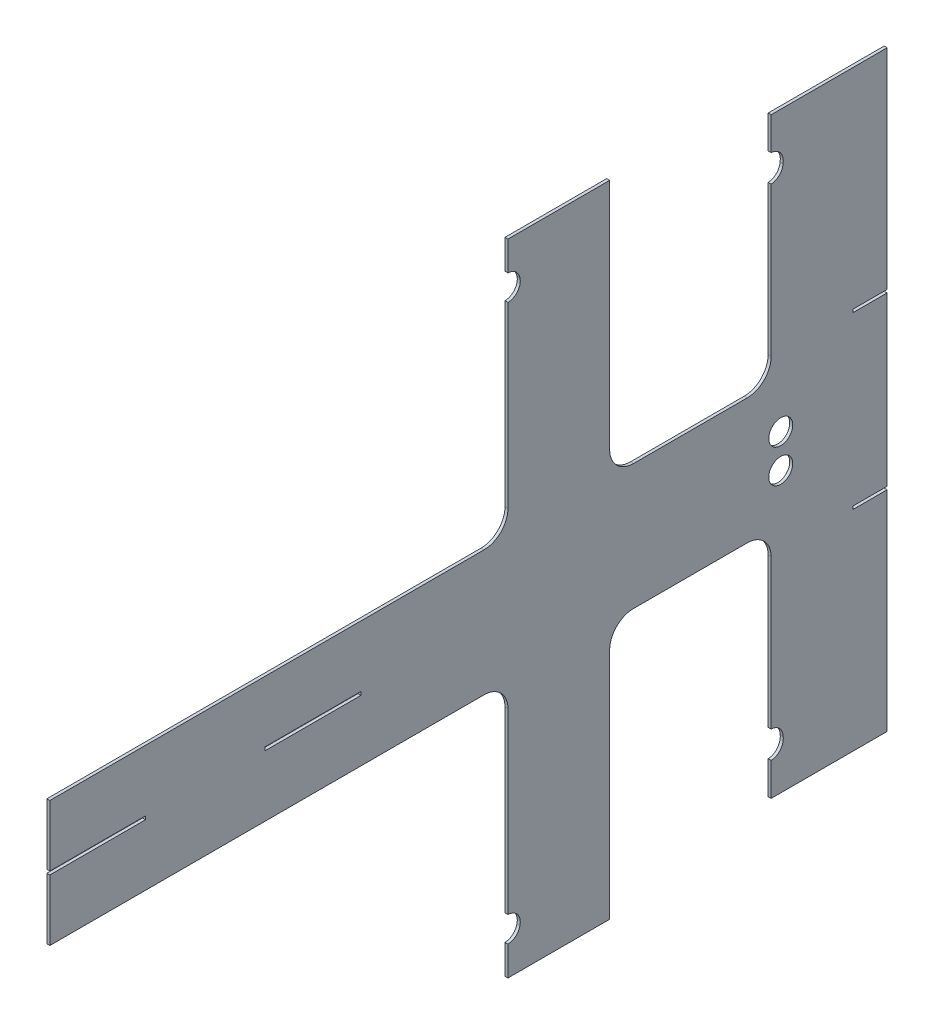
SolidWorks part; units mm, degrees
material "Custom Plastic"
ref_plane "X-Y Datum" through (0, 0, 0) normal (0, 0, 1) x (1, 0, 0)
ref_plane "X-Z Datum" through (0, 0, 0) normal (0, 1, 0) x (1, 0, 0)
ref_plane "Y-Z Datum" through (0, 0, 0) normal (1, 0, 0) x (0, 0, -1)
ref_plane "Plane1" through (523.5321, 0, 0) normal (-1, 0, 0) x (0, 0, 1)
sketch "Sketch1" plane through (523.5321, 0, 0) normal (-1, 0, 0) x (0, 0, 1)
  line L0 (-139.7, 314.325) -> (-16.51, 314.325)
  line L1 (-16.51, 314.325) -> (-16.51, 66.675)
  line L2 (-103.1775, -92.075) -> (-103.1775, -88.9)
  line L3 (-103.1775, 88.9) -> (-103.1775, 92.075)
  line L4 (-103.1775, -88.9) -> (-139.7, -88.9)
  line L5 (-139.7, -88.9) -> (-139.7, 88.9)
  line L6 (-139.7, 88.9) -> (-103.1775, 88.9)
  line L7 (-103.1775, 92.075) -> (-139.7, 92.075)
  line L8 (-103.1775, -92.075) -> (-139.7, -92.075)
  line L9 (-139.7, 92.075) -> (-139.7, 314.325)
  line L10 (-139.7, -92.075) -> (-139.7, -314.325)
  line L11 (-139.7, -314.325) -> (-16.51, -314.325)
  line L12 (-16.51, -314.325) -> (-16.51, -66.675)
  line L13 (-16.51, -66.675) -> (154.94, -66.675)
  line L14 (749.3, -66.675) -> (749.3, 66.675)
  line L15 (749.3, 66.675) -> (262.89, 66.675)
  line L16 (262.89, 339.725) -> (262.89, 66.675)
  line L17 (262.89, 339.725) -> (154.94, 339.725)
  line L18 (154.94, 339.725) -> (154.94, 66.675)
  line L19 (262.89, -66.675) -> (262.89, -339.725)
  line L20 (262.89, -339.725) -> (154.94, -339.725)
  line L21 (154.94, -339.725) -> (154.94, -66.675)
  line L22 (262.89, -66.675) -> (749.3, -66.675)
  line L23 (154.94, 66.675) -> (-16.51, 66.675)
  dimension "D1" = 177.8
  dimension "D2" = 184.15
  dimension "D3" = 36.5225
  dimension "D4" = 36.5225
  dimension "D5" = 3.175
  dimension "D6" = 3.175
  dimension "D7" = 222.25
  dimension "D8" = 123.19
  dimension "D9" = 247.65
  dimension "D10" = 222.25
  dimension "D11" = 171.45
  dimension "D12" = 279.4
  dimension "D13" = 107.95
  dimension "D14" = 273.05
extrude "Boss-Extrude1" add sketch "Sketch1" along normal mid plane 3.175 contours L15 L16 L17 L18 L23 L1 L0 L9 L7 L3 L6 L5 L4 L2 L8 L10 L11 L12 L13 L21 L20 L19 L22 L14
ref_plane "Plane2" through (906.3228, 136.1666, 0) normal (0.9471, -0.3184, 0.0399) x (0.0378, -0.0127, -0.9992)
sketch "Sketch2" plane through (906.3228, 136.1666, 0) normal (0.9471, -0.3184, 0.0399) x (0.0378, -0.0127, -0.9992)
  circle A0 centre (0, 0) radius 13.081
  dimension "D1" = 26.162
extrude "Cut-Extrude1" cut sketch "Sketch2" against normal up to surface (410.2408 mm away)
sketch "Sketch5" plane through (525.1196, 0, 0) normal (1, 0, 0) x (0, 0, -1)
  ellipse E0 centre (16.0688, 264.3155) end of major axis (16.51, 250.5304) minor radius 13.2132
extrude "Cut-Extrude3" cut sketch "Sketch5" against normal through all
sketch "Sketch7" plane through (521.9446, 0, 0) normal (-1, 0, 0) x (0, 0, 1)
  ellipse E0 centre (-16.2026, 265.3828) end of major axis (-16.51, 279.1825) minor radius 13.0881
extrude "Cut-Extrude6" cut sketch "Sketch7" against normal through all
sketch "Sketch9" plane through (525.1196, 0, 0) normal (1, 0, 0) x (0, 0, -1)
  line L1 (16.51, 314.325) -> (16.51, 279.1825) construction
  ellipse E0 centre (16.2026, 265.3828) end of major axis (16.51, 279.366) minor radius 13.2029
extrude "Cut-Extrude9" cut sketch "Sketch9" against normal through all
ref_plane "Plane3" through (906.3228, 241.3, 254) normal (-0.9901, 0.1386, 0.0235) x (0.0233, -0.0033, 0.9997)
sketch "Sketch10" plane through (906.3228, 241.3, 254) normal (-0.9901, 0.1386, 0.0235) x (0.0233, -0.0033, 0.9997)
  circle A0 centre (0, 0) radius 13.081
  dimension "D1" = 26.162
extrude "Cut-Extrude10" cut sketch "Sketch10" along normal up to surface (386.4019 mm away)
sketch "Sketch12" plane through (525.1196, 0, 0) normal (1, 0, 0) x (0, 0, -1)
  ellipse E0 centre (-263.0633, 294.6624) end of major axis (-262.89, 281.4545) minor radius 13.0841
extrude "Cut-Extrude11" cut sketch "Sketch12" against normal through all
sketch "Sketch13" plane through (521.9446, 0, 0) normal (-1, 0, 0) x (0, 0, 1)
  line L0 (262.89, 339.725) -> (262.89, 308.3121) construction
  ellipse E0 centre (263.1388, 295.1069) end of major axis (262.89, 308.5494) minor radius 13.1927
extrude "Cut-Extrude12" cut sketch "Sketch13" against normal through all
sketch "Sketch15" plane through (525.1196, 0, 0) normal (1, 0, 0) x (0, 0, -1)
  line L0 (-262.89, 281.4545) -> (-262.89, 66.675) construction
  ellipse E0 centre (-263.0633, 294.6624) end of major axis (-262.89, 281.4162) minor radius 13.2333
extrude "Cut-Extrude13" cut sketch "Sketch15" against normal through all
mirror "Mirror1" about plane through (0, 0, 0) normal (0, 1, 0) of "Cut-Extrude13", "Cut-Extrude12", "Cut-Extrude11", "Cut-Extrude10", "Cut-Extrude9", "Cut-Extrude6", "Cut-Extrude3", "Cut-Extrude1"
fillet "Fillet1" radius 25.4 6 edges at (523.5321, 66.675, 262.89) (523.5321, -66.675, 262.89) (523.5321, -66.675, 154.94) (523.5321, -66.675, -16.51) (523.5321, 66.675, 154.94) (523.5321, 66.675, -16.51)
sketch "Sketch16" plane through (525.1196, 0, 0) normal (1, 0, 0) x (0, 0, -1)
  line L0 (-520.7, 0) -> (-419.1, 0) construction
  line L1 (-419.1, -1.7907) -> (-419.1, 1.7907)
  line L2 (-520.7, -1.7907) -> (-520.7, 1.7907)
  line L3 (-520.7, 1.7907) -> (-419.1, 1.7907)
  line L4 (-419.1, -1.7907) -> (-520.7, -1.7907)
  line L28 (-262.89, -308.5494) -> (-262.89, -339.725)
  line L29 (-262.89, -339.725) -> (-154.94, -339.725)
  line L30 (-154.94, -339.725) -> (-154.94, -92.075)
  line L31 (-129.54, -66.675) -> (-8.89, -66.675)
  line L32 (16.51, -92.075) -> (16.51, -250.5304)
  line L33 (16.51, -279.366) -> (16.51, -314.325)
  line L34 (16.51, -314.325) -> (139.7, -314.325)
  line L35 (139.7, -314.325) -> (139.7, -92.075)
  line L36 (139.7, -92.075) -> (103.1775, -92.075)
  line L37 (103.1775, -92.075) -> (103.1775, -88.9)
  line L38 (103.1775, -88.9) -> (139.7, -88.9)
  line L39 (139.7, -88.9) -> (139.7, 88.9)
  line L40 (139.7, 88.9) -> (103.1775, 88.9)
  line L41 (103.1775, 88.9) -> (103.1775, 92.075)
  line L42 (103.1775, 92.075) -> (139.7, 92.075)
  line L43 (139.7, 92.075) -> (139.7, 314.325)
  line L44 (139.7, 314.325) -> (16.51, 314.325)
  line L45 (16.51, 314.325) -> (16.51, 279.366)
  line L46 (16.51, 250.5304) -> (16.51, 92.075)
  line L47 (-8.89, 66.675) -> (-129.54, 66.675)
  line L48 (-154.94, 92.075) -> (-154.94, 339.725)
  line L49 (-154.94, 339.725) -> (-262.89, 339.725)
  line L50 (-262.89, 339.725) -> (-262.89, 308.5494)
  line L51 (-262.89, 281.4162) -> (-262.89, 92.075)
  line L52 (-288.29, 66.675) -> (-749.3, 66.675)
  line L53 (-749.3, 66.675) -> (-749.3, -66.675)
  line L54 (-749.3, -66.675) -> (-288.29, -66.675)
  line L55 (-262.89, -92.075) -> (-262.89, -281.4162)
  line L56 (-262.89, -308.5494) -> (-262.89, -339.725)
  line L57 (-262.89, -339.725) -> (-154.94, -339.725)
  line L58 (-154.94, -339.725) -> (-154.94, -92.075)
  line L59 (-129.54, -66.675) -> (-8.89, -66.675)
  line L60 (16.51, -92.075) -> (16.51, -250.5304)
  line L61 (16.51, -279.366) -> (16.51, -314.325)
  line L62 (16.51, -314.325) -> (139.7, -314.325)
  line L63 (139.7, -314.325) -> (139.7, -92.075)
  line L64 (139.7, -92.075) -> (103.1775, -92.075)
  line L65 (103.1775, -92.075) -> (103.1775, -88.9)
  line L66 (103.1775, -88.9) -> (139.7, -88.9)
  line L67 (139.7, -88.9) -> (139.7, 88.9)
  line L68 (139.7, 88.9) -> (103.1775, 88.9)
  line L69 (103.1775, 88.9) -> (103.1775, 92.075)
  line L70 (103.1775, 92.075) -> (139.7, 92.075)
  line L71 (139.7, 92.075) -> (139.7, 314.325)
  line L72 (139.7, 314.325) -> (16.51, 314.325)
  line L73 (16.51, 314.325) -> (16.51, 279.366)
  line L74 (16.51, 250.5304) -> (16.51, 92.075)
  line L75 (-8.89, 66.675) -> (-129.54, 66.675)
  line L76 (-154.94, 92.075) -> (-154.94, 339.725)
  line L77 (-154.94, 339.725) -> (-262.89, 339.725)
  line L78 (-262.89, 339.725) -> (-262.89, 308.5494)
  line L79 (-262.89, 281.4162) -> (-262.89, 92.075)
  line L80 (-288.29, 66.675) -> (-749.3, 66.675)
  line L81 (-749.3, 66.675) -> (-749.3, -66.675)
  line L82 (-749.3, -66.675) -> (-288.29, -66.675)
  line L83 (-262.89, -92.075) -> (-262.89, -281.4162)
  arc A6 (-129.54, -66.675) -> (-154.94, -92.075) centre (-129.54, -92.075) ccw
  arc A7 (16.51, -92.075) -> (-8.89, -66.675) centre (-8.89, -92.075) ccw
  arc A8 (-8.89, 66.675) -> (16.51, 92.075) centre (-8.89, 92.075) ccw
  arc A9 (-154.94, 92.075) -> (-129.54, 66.675) centre (-129.54, 92.075) ccw
  arc A10 (-288.29, 66.675) -> (-262.89, 92.075) centre (-288.29, 92.075) ccw
  arc A11 (-262.89, -92.075) -> (-288.29, -66.675) centre (-288.29, -92.075) ccw
  arc A12 (-129.54, -66.675) -> (-154.94, -92.075) centre (-129.54, -92.075) ccw
  arc A13 (16.51, -92.075) -> (-8.89, -66.675) centre (-8.89, -92.075) ccw
  arc A14 (-8.89, 66.675) -> (16.51, 92.075) centre (-8.89, 92.075) ccw
  arc A15 (-154.94, 92.075) -> (-129.54, 66.675) centre (-129.54, 92.075) ccw
  arc A16 (-288.29, 66.675) -> (-262.89, 92.075) centre (-288.29, 92.075) ccw
  arc A17 (-262.89, -92.075) -> (-288.29, -66.675) centre (-288.29, -92.075) ccw
  ellipse E8 centre (-263.0633, -294.6624) end of major axis (-262.89, -281.4162) minor radius 13.2333 (-250.2346, -297.9127) -> (-262.89, -281.4162) ccw
  ellipse E9 centre (-263.1388, -295.1069) end of major axis (-262.89, -308.5494) minor radius 13.1927 (-262.89, -308.5494) -> (-250.2346, -297.9127) ccw
  ellipse E10 centre (16.0688, -264.3155) end of major axis (16.51, -250.5304) minor radius 13.2132 (29.2455, -263.2443) -> (16.51, -250.5304) ccw
  ellipse E11 centre (16.2026, -265.3828) end of major axis (16.51, -279.366) minor radius 13.2029 (16.51, -279.366) -> (29.2455, -263.2443) ccw
  ellipse E12 centre (16.2026, 265.3828) end of major axis (16.51, 279.366) minor radius 13.2029 (29.2455, 263.2443) -> (16.51, 279.366) ccw
  ellipse E13 centre (16.0688, 264.3155) end of major axis (16.51, 250.5304) minor radius 13.2132 (16.51, 250.5304) -> (29.2455, 263.2443) ccw
  ellipse E14 centre (-263.1388, 295.1069) end of major axis (-262.89, 308.5494) minor radius 13.1927 (-250.2346, 297.9127) -> (-262.89, 308.5494) ccw
  ellipse E15 centre (-263.0633, 294.6624) end of major axis (-262.89, 281.4162) minor radius 13.2333 (-262.89, 281.4162) -> (-250.2346, 297.9127) ccw
  ellipse E16 centre (-263.0633, -294.6624) end of major axis (-262.89, -281.4162) minor radius 13.2333 (-250.2346, -297.9127) -> (-262.89, -281.4162) ccw
  ellipse E17 centre (-263.1388, -295.1069) end of major axis (-262.89, -308.5494) minor radius 13.1927 (-262.89, -308.5494) -> (-250.2346, -297.9127) ccw
  ellipse E18 centre (16.0688, -264.3155) end of major axis (16.51, -250.5304) minor radius 13.2132 (29.2455, -263.2443) -> (16.51, -250.5304) ccw
  ellipse E19 centre (16.2026, -265.3828) end of major axis (16.51, -279.366) minor radius 13.2029 (16.51, -279.366) -> (29.2455, -263.2443) ccw
  ellipse E20 centre (16.2026, 265.3828) end of major axis (16.51, 279.366) minor radius 13.2029 (29.2455, 263.2443) -> (16.51, 279.366) ccw
  ellipse E21 centre (16.0688, 264.3155) end of major axis (16.51, 250.5304) minor radius 13.2132 (16.51, 250.5304) -> (29.2455, 263.2443) ccw
  ellipse E22 centre (-263.1388, 295.1069) end of major axis (-262.89, 308.5494) minor radius 13.1927 (-250.2346, 297.9127) -> (-262.89, 308.5494) ccw
  ellipse E23 centre (-263.0633, 294.6624) end of major axis (-262.89, 281.4162) minor radius 13.2333 (-262.89, 281.4162) -> (-250.2346, 297.9127) ccw
  point P2 (-520.7, 0)
  point P10 (-419.1, 0)
  point P13 (-520.7, 0)
  dimension "D2" = 101.6
  dimension "D3" = 3.5814
  dimension "D4" = 3.5814
  dimension "D1" = 0
extrude "Cut-Extrude15" cut sketch "Sketch16" against normal through all contours L2 L0 L1 L3 | L0 L2 L4 L1
sketch "Sketch17" plane through (525.1196, 0, 0) normal (1, 0, 0) x (0, 0, -1)
  line L0 (-749.3, 0) -> (-647.7, 0) construction
  line L1 (-749.3, -66.675) -> (-749.3, 66.675) construction
  line L2 (-647.7, 1.7907) -> (-647.7, -1.7907)
  line L3 (-647.7, 1.7907) -> (-749.3, 1.7907)
  line L4 (-647.7, -1.7907) -> (-749.3, -1.7907)
  line L5 (-749.3, -1.7907) -> (-749.3, 1.7907)
  point P7 (-647.7, 0)
  dimension "D1" = 101.6
  dimension "D2" = 3.5814
extrude "Cut-Extrude16" cut sketch "Sketch17" against normal through all contours L3 L5 L4 L2
sketch "Sketch18" plane through (525.1196, 0, 0) normal (1, 0, 0) x (0, 0, -1)
  line L0 (1.7463, 0) -> (-1.7463, 0) construction
  ellipse E1 centre (26.7153, 17.7791) end of major axis (27.7698, 30.5832) minor radius 12.7
  ellipse E2 centre (26.7153, -17.7791) end of major axis (27.7698, -30.5832) minor radius 12.7
extrude "Cut-Extrude17" cut sketch "Sketch18" against normal through all
